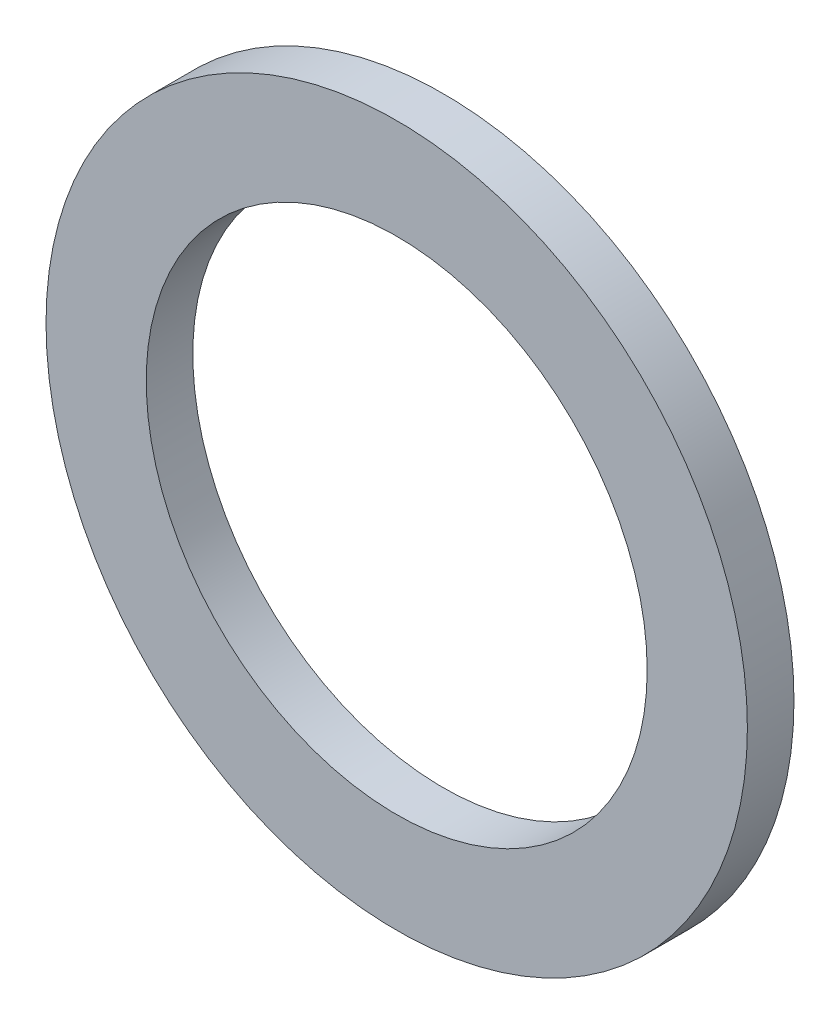
SolidWorks part; units mm, degrees
ref_plane "Front Plane" through (0, 0, 0) normal (0, 0, 1) x (1, 0, 0)
ref_plane "Top Plane" through (0, 0, 0) normal (0, 1, 0) x (1, 0, 0)
ref_plane "Right Plane" through (0, 0, 0) normal (1, 0, 0) x (0, 0, -1)
sketch "Sketch1" plane through (0, 0, 0) normal (0, 0, 1) x (1, 0, 0)
  circle A0 centre (0, 0) radius 5
  circle A1 centre (0, 0) radius 7
  dimension "D1" = 10
  dimension "D2" = 14
extrude "Boss-Extrude1" add sketch "Sketch1" along normal blind 0.93
